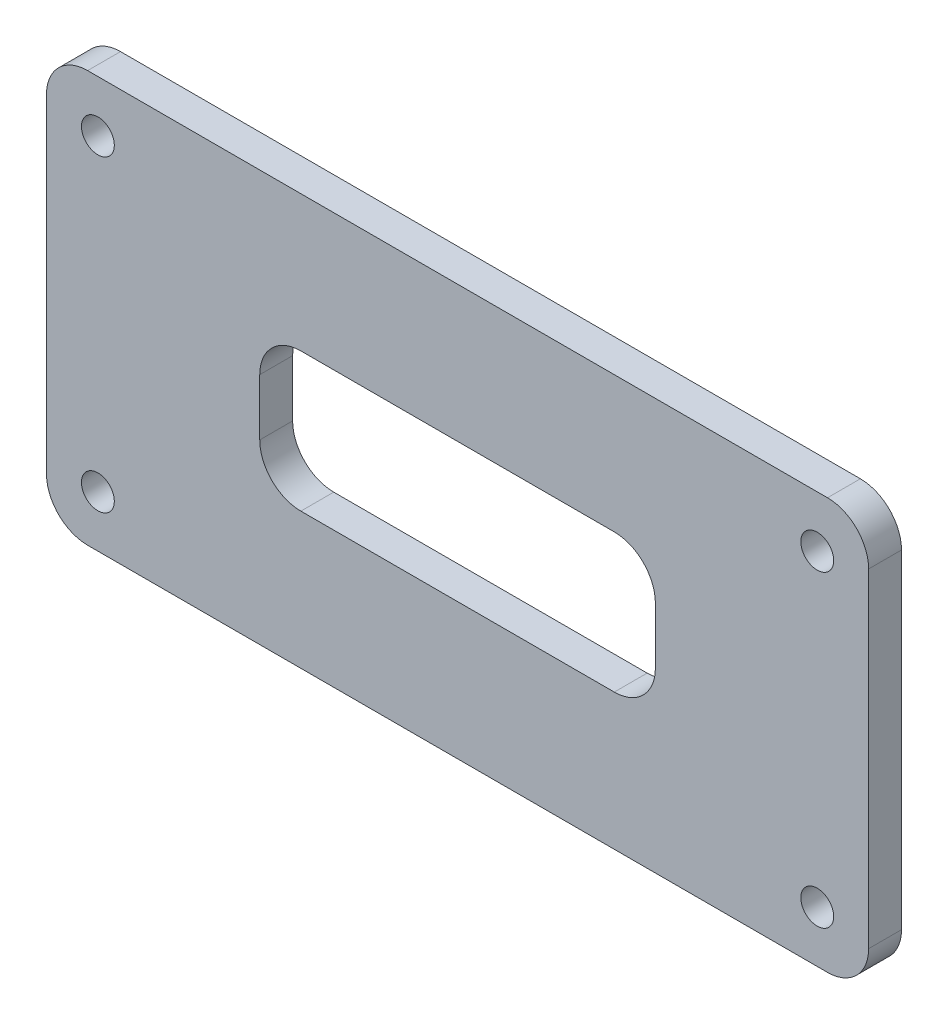
SolidWorks part; units mm, degrees
ref_plane "前视基准面" through (0, 0, 0) normal (0, 0, 1) x (1, 0, 0)
ref_plane "上视基准面" through (0, 0, 0) normal (0, 1, 0) x (1, 0, 0)
ref_plane "右视基准面" through (0, 0, 0) normal (1, 0, 0) x (0, 0, -1)
sketch "草图1" plane through (0, 0, 0) normal (0, 0, 1) x (1, 0, 0)
  line L0 (-36, -20) -> (36, -20)
  line L1 (-36, 20) -> (36, 20)
  line L2 (40, 16) -> (40, -16)
  line L3 (-40, 16) -> (-40, -16)
  arc A0 (36, -20) -> (40, -16) centre (36, -16) ccw
  arc A1 (-40, -16) -> (-36, -20) centre (-36, -16) ccw
  arc A2 (40, 16) -> (36, 20) centre (36, 16) ccw
  arc A3 (-36, 20) -> (-40, 16) centre (-36, 16) ccw
extrude "凸台-拉伸1" add sketch "草图1" against normal blind 3.2
sketch "草图2" plane through (0, 0, 0) normal (0, 0, 1) x (1, 0, 0)
  line L0 (-15.25, -6.75) -> (15.25, -6.75)
  line L1 (-15.25, 6.75) -> (15.25, 6.75)
  line L2 (19.25, 2.75) -> (19.25, -2.75)
  line L3 (-19.25, 2.75) -> (-19.25, -2.75)
  arc A0 (-19.25, -2.75) -> (-15.25, -6.75) centre (-15.25, -2.75) ccw
  arc A1 (19.25, 2.75) -> (15.25, 6.75) centre (15.25, 2.75) ccw
  arc A2 (15.25, -6.75) -> (19.25, -2.75) centre (15.25, -2.75) ccw
  arc A3 (-15.25, 6.75) -> (-19.25, 2.75) centre (-15.25, 2.75) ccw
extrude "切除-拉伸1" cut sketch "草图2" against normal blind 3.2
sketch "草图3" plane through (0, 0, 0) normal (0, 0, 1) x (1, 0, 0)
  circle A0 centre (-35, 15) radius 1.6
  circle A1 centre (35, 15) radius 1.6
  circle A2 centre (35, -15) radius 1.6
  circle A3 centre (-35, -15) radius 1.6
extrude "切除-拉伸2" cut sketch "草图3" against normal blind 3.2
